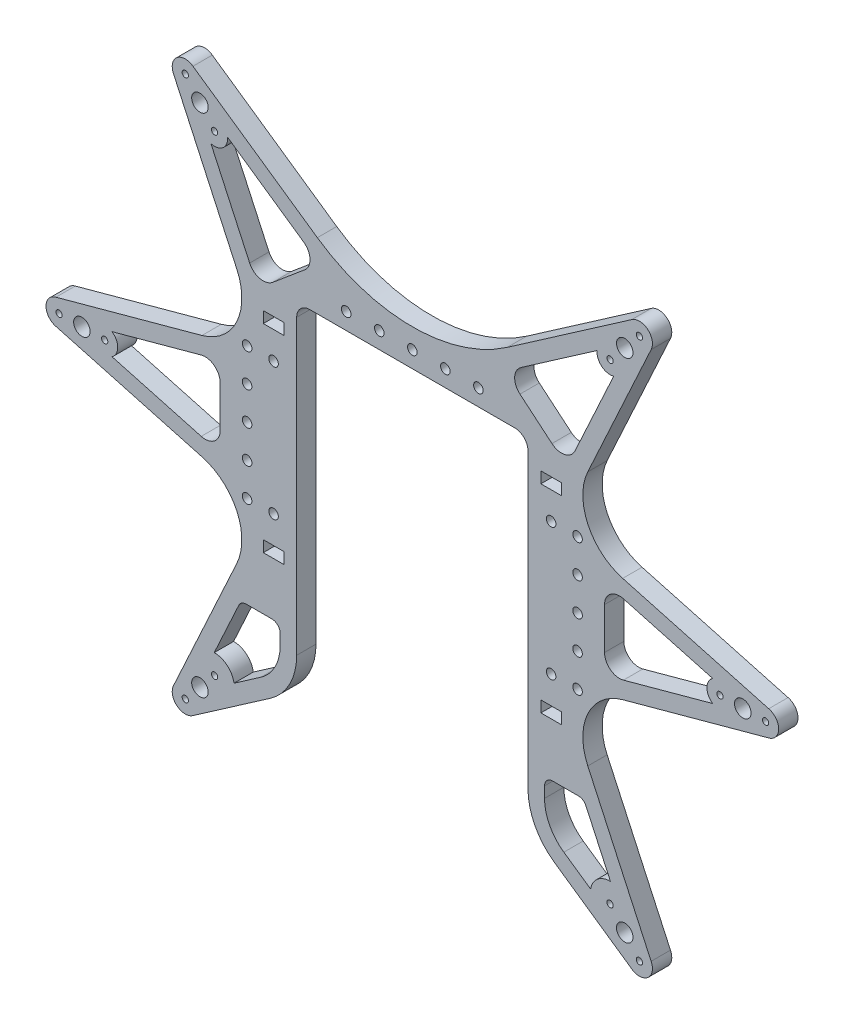
SolidWorks part; units mm, degrees
material "Acrylic (Medium-high impact)"
ref_plane "Front Plane" through (0, 0, 0) normal (0, 0, 1) x (1, 0, 0)
ref_plane "Top Plane" through (0, 0, 0) normal (0, 1, 0) x (1, 0, 0)
ref_plane "Right Plane" through (0, 0, 0) normal (1, 0, 0) x (0, 0, -1)
sketch "Sketch1" plane through (0, 0, 0) normal (0, 0, 1) x (1, 0, 0)
  line L0 (587.1768, 489.0962) -> (587.1768, 412.0041) construction
  line L1 (549.3782, 453.8298) -> (576.3894, 461.205)
  line L2 (601.3767, 418.8158) -> (595.1767, 422.2158) construction
  line L3 (590.0159, 402.7396) -> (597.7767, 402.7396)
  line L4 (600.2767, 396.9582) -> (600.2767, 400.2396)
  line L5 (601.3767, 422.2158) -> (595.1767, 418.8158) construction
  line L6 (532.4267, 446.7161) -> (532.4267, 450.5502) construction
  line L7 (576.6167, 434.6502) -> (532.4267, 446.7161)
  line L8 (635.7171, 455.9841) -> (-31503.6634, 38758.2062) construction
  line L9 (532.4267, 450.5502) -> (532.4267, 454.3842) construction
  line L10 (601.3767, 422.2158) -> (601.3767, 418.8158)
  line L11 (601.3767, 422.2158) -> (595.1767, 422.2158)
  line L12 (595.1767, 422.2158) -> (595.1767, 418.8158)
  line L13 (549.3782, 447.2706) -> (576.3894, 439.8953)
  line L14 (575.9979, 527.1546) -> (571.5627, 532.4403) construction
  line L15 (575.9979, 527.1546) -> (580.4331, 521.8689) construction
  line L16 (601.3767, 418.8158) -> (595.1767, 418.8158)
  line L17 (576.6167, 466.4501) -> (576.6167, 434.6502) construction
  line L18 (694.2433, 380.1612) -> (686.125, 385.7883)
  line L19 (570.952, 533.1681) -> (573.8891, 535.6326) construction
  line L20 (-358.0106, 400.5502) -> (49641.9894, 400.5502) construction
  line L21 (540.2767, 450.5502) -> (547.1767, 450.5502) construction
  line L22 (-351.1587, 450.5502) -> (49648.8413, 450.5502) construction
  line L23 (680.2767, 396.9582) -> (680.2767, 400.2396)
  line L24 (582.1207, 456.8289) -> (582.1207, 444.2715)
  line L25 (685.3767, 482.2502) -> (679.1767, 478.8502) construction
  line L26 (587.1768, 489.0962) -> (568.0149, 530.7036)
  line L27 (690.5374, 402.7396) -> (682.7767, 402.7396)
  line L28 (700.2251, 385.1805) -> (692.8082, 401.2854)
  line L29 (685.3767, 478.8502) -> (679.1767, 482.2502) construction
  line L30 (611.5369, 509.5368) -> (573.8891, 535.6326)
  line L31 (568.0149, 530.7036) -> (570.952, 533.1681) construction
  line L32 (610.8062, 450.5502) -> (605.2767, 450.5502) construction
  line L33 (605.2767, 489.5502) -> (675.2767, 489.5502)
  line L34 (663.4579, 478.1765) -> (-31475.9226, -37824.0456) construction
  line L35 (540.2767, 450.5502) -> (533.3767, 450.5502) construction
  line L36 (576.6167, 466.4501) -> (532.4267, 454.3842)
  line L37 (575.9979, 373.9457) -> (571.5627, 368.66) construction
  line L38 (683.2767, 381.679) -> (706.6642, 365.4678)
  line L39 (709.6013, 367.9323) -> (712.5384, 370.3968) construction
  line L40 (580.3282, 385.1805) -> (587.7451, 401.2854)
  line L41 (640.2767, 450.5502) -> (675.2767, 450.5502) construction
  line L42 (706.6642, 365.4678) -> (709.6013, 367.9323) construction
  line L43 (704.5554, 373.9457) -> (700.1202, 379.2314) construction
  line L44 (704.5554, 373.9457) -> (708.9906, 368.66) construction
  line L45 (740.2767, 450.5502) -> (747.1767, 450.5502) construction
  line L46 (586.31, 380.1612) -> (594.4283, 385.7883)
  line L47 (669.7471, 450.5502) -> (675.2767, 450.5502) construction
  line L48 (575.9979, 373.9457) -> (580.4331, 379.2314) construction
  line L49 (587.1768, 412.0041) -> (568.0149, 370.3968)
  line L50 (712.5384, 530.7036) -> (709.6013, 533.1681) construction
  line L51 (740.2767, 450.5502) -> (733.3767, 450.5502) construction
  line L52 (573.8891, 365.4678) -> (570.952, 367.9323) construction
  line L53 (570.952, 367.9323) -> (568.0149, 370.3968) construction
  line L54 (709.6013, 533.1681) -> (706.6642, 535.6326) construction
  line L55 (597.2767, 381.679) -> (573.8891, 365.4678)
  line L56 (703.9366, 466.4501) -> (703.9366, 434.6502) construction
  line L58 (704.5554, 527.1546) -> (700.1202, 521.8689) construction
  line L59 (704.5554, 527.1546) -> (708.9906, 532.4403) construction
  line L60 (748.1267, 450.5502) -> (748.1267, 454.3842) construction
  line L61 (748.1267, 446.7161) -> (748.1267, 450.5502) construction
  line L62 (1630.6528, 450.5502) -> (-48369.3472, 450.5502) construction
  line L63 (691.7267, 450.5502) -> (588.8267, 450.5502) construction
  line L64 (679.1767, 422.2158) -> (685.3767, 418.8158) construction
  line L67 (693.3765, 489.0962) -> (693.3765, 412.0041) construction
  line L68 (-358.708, 500.5502) -> (49641.292, 500.5502) construction
  line L69 (579.336, 518.0744) -> (591.0486, 492.6418)
  line L70 (679.1767, 418.8158) -> (685.3767, 422.2158) construction
  line L71 (685.3767, 478.8502) -> (685.3767, 482.2502)
  line L72 (605.2767, 489.5502) -> (605.2767, 396.9582)
  line L73 (584.3606, 522.2905) -> (607.3728, 506.3395)
  line L74 (607.7017, 499.196) -> (598.0264, 491.0775)
  line L75 (685.3767, 478.8502) -> (679.1767, 478.8502)
  line L76 (679.1767, 478.8502) -> (679.1767, 482.2502)
  line L77 (672.8516, 499.196) -> (682.5269, 491.0775)
  line L78 (696.1927, 522.2905) -> (673.1805, 506.3395)
  line L79 (675.2767, 489.5502) -> (675.2767, 396.9582)
  line L81 (701.2173, 518.0744) -> (689.5047, 492.6418)
  line L83 (693.3765, 412.0041) -> (712.5384, 370.3968)
  line L87 (703.9366, 466.4501) -> (748.1267, 454.3842)
  line L88 (669.0164, 509.5368) -> (706.6642, 535.6326)
  line L89 (693.3765, 489.0962) -> (712.5384, 530.7036)
  line L90 (698.4326, 456.8289) -> (698.4326, 444.2715)
  line L91 (685.3767, 482.2502) -> (679.1767, 482.2502)
  line L92 (731.1751, 447.2706) -> (704.1639, 439.8953)
  line L93 (679.1767, 418.8158) -> (685.3767, 418.8158)
  line L94 (685.3767, 422.2158) -> (685.3767, 418.8158)
  line L95 (679.1767, 422.2158) -> (685.3767, 422.2158)
  line L96 (703.9366, 434.6502) -> (748.1267, 446.7161)
  line L97 (731.1751, 453.8298) -> (704.1639, 461.205)
  line L98 (679.1767, 422.2158) -> (679.1767, 418.8158)
  line L100 (590.2767, 450.5502) -> (590.2767, 460.5502) construction
  line L102 (640.2767, 494.5502) -> (630.2767, 494.5502) construction
  line L104 (568.9811, 521.2669) -> (581.557, 531.8192) construction
  line L111 (640.2767, -500.116) -> (640.2767, 49499.884) construction
  line L157 (595.1767, 482.2502) -> (601.3767, 482.2502)
  line L158 (601.3767, 478.8502) -> (601.3767, 482.2502)
  line L159 (595.1767, 478.8502) -> (601.3767, 482.2502) construction
  line L162 (595.1767, 482.2502) -> (601.3767, 478.8502) construction
  line L163 (595.1767, 478.8502) -> (601.3767, 478.8502)
  line L164 (595.1767, 478.8502) -> (595.1767, 482.2502)
  circle A0 centre (533.3767, 450.5502) radius 0.95
  arc A1 (582.1207, 444.2715) -> (576.3894, 439.8953) centre (577.5843, 444.2715) cw
  circle A2 centre (575.9979, 527.1546) radius 2.5
  circle A3 centre (547.1767, 450.5502) radius 0.95
  arc A4 (549.3782, 447.2706) -> (549.3782, 453.8298) centre (547.1767, 450.5502) ccw
  circle A5 centre (540.2767, 450.5502) radius 2.5
  arc A6 (532.4267, 446.7161) -> (532.4267, 454.3842) centre (533.3767, 450.5502) cw
  circle A7 centre (590.2767, 460.5502) radius 1.45
  circle A8 centre (571.5627, 532.4403) radius 0.95
  circle A9 centre (580.4331, 521.8689) radius 0.95
  arc A10 (579.336, 518.0744) -> (584.3606, 522.2905) centre (580.4331, 521.8689) ccw
  arc A11 (582.1207, 456.8289) -> (576.3894, 461.205) centre (577.5843, 456.8289) ccw
  arc A12 (600.2767, 400.2396) -> (597.7767, 402.7396) centre (597.7767, 400.2396) ccw
  circle A13 centre (682.2767, 470.5502) radius 1.45
  arc A14 (586.31, 380.1612) -> (580.3282, 385.1805) centre (580.4331, 379.2314) ccw
  arc A15 (568.0149, 530.7036) -> (573.8891, 535.6326) centre (571.5627, 532.4403) cw
  arc A16 (605.2767, 396.9582) -> (597.2767, 381.679) centre (586.6858, 396.9582) cw
  arc A17 (600.2767, 396.9582) -> (594.4283, 385.7883) centre (586.6858, 396.9582) cw
  arc A18 (587.7451, 401.2854) -> (590.0159, 402.7396) centre (590.0159, 400.2396) cw
  arc A19 (675.2767, 396.9582) -> (683.2767, 381.679) centre (693.8675, 396.9582) ccw
  circle A20 centre (630.2767, 494.5502) radius 1.45
  circle A21 centre (620.2767, 494.5502) radius 1.45
  arc A22 (680.2767, 396.9582) -> (686.125, 385.7883) centre (693.8675, 396.9582) ccw
  arc A23 (680.2767, 400.2396) -> (682.7767, 402.7396) centre (682.7767, 400.2396) cw
  arc A24 (692.8082, 401.2854) -> (690.5374, 402.7396) centre (690.5374, 400.2396) ccw
  arc A25 (694.2433, 380.1612) -> (700.2251, 385.1805) centre (700.1202, 379.2314) cw
  circle A27 centre (580.4331, 379.2314) radius 0.95
  circle A28 centre (575.9979, 373.9457) radius 2.5
  circle A29 centre (571.5627, 368.66) radius 0.95
  arc A30 (573.8891, 365.4678) -> (568.0149, 370.3968) centre (571.5627, 368.66) cw
  arc A31 (611.5369, 509.5368) -> (669.0164, 509.5368) centre (640.2767, 550.9991) ccw
  arc A35 (576.6167, 434.6502) -> (587.1768, 412.0041) centre (572.3036, 418.8538) cw
  arc A36 (598.0264, 491.0775) -> (591.0486, 492.6418) centre (595.1348, 494.5236) cw
  arc A37 (607.7017, 499.196) -> (607.3728, 506.3395) centre (604.8101, 502.6422) ccw
  arc A38 (576.6167, 466.4501) -> (587.1768, 489.0962) centre (572.3036, 482.2466) ccw
  circle A40 centre (590.2767, 430.5502) radius 1.45
  circle A42 centre (590.2767, 440.5502) radius 1.45
  arc A44 (703.9366, 466.4501) -> (693.3765, 489.0962) centre (708.2497, 482.2466) cw
  arc A45 (672.8516, 499.196) -> (673.1805, 506.3395) centre (675.7432, 502.6422) cw
  arc A46 (682.5269, 491.0775) -> (689.5047, 492.6418) centre (685.4185, 494.5236) ccw
  arc A47 (703.9366, 434.6502) -> (693.3765, 412.0041) centre (708.2497, 418.8538) ccw
  circle A49 centre (590.2767, 470.5502) radius 1.45
  circle A50 centre (682.2767, 430.5502) radius 1.45
  arc A51 (706.6642, 365.4678) -> (712.5384, 370.3968) centre (708.9906, 368.66) ccw
  circle A52 centre (708.9906, 368.66) radius 0.95
  circle A53 centre (704.5554, 373.9457) radius 2.5
  circle A54 centre (700.1202, 379.2314) radius 0.95
  circle A58 centre (660.2767, 494.5502) radius 1.45
  circle A59 centre (650.2767, 494.5502) radius 1.45
  arc A63 (712.5384, 530.7036) -> (706.6642, 535.6326) centre (708.9906, 532.4403) ccw
  arc A66 (698.4326, 456.8289) -> (704.1639, 461.205) centre (702.969, 456.8289) cw
  arc A67 (701.2173, 518.0744) -> (696.1927, 522.2905) centre (700.1202, 521.8689) cw
  circle A68 centre (700.1202, 521.8689) radius 0.95
  circle A69 centre (708.9906, 532.4403) radius 0.95
  circle A70 centre (690.2767, 450.5502) radius 1.45
  arc A71 (748.1267, 446.7161) -> (748.1267, 454.3842) centre (747.1767, 450.5502) ccw
  circle A72 centre (740.2767, 450.5502) radius 2.5
  arc A74 (731.1751, 447.2706) -> (731.1751, 453.8298) centre (733.3767, 450.5502) cw
  circle A75 centre (733.3767, 450.5502) radius 0.95
  circle A76 centre (704.5554, 527.1546) radius 2.5
  arc A77 (698.4326, 444.2715) -> (704.1639, 439.8953) centre (702.969, 444.2715) ccw
  circle A78 centre (747.1767, 450.5502) radius 0.95
  circle A81 centre (690.2767, 470.5502) radius 1.45
  circle A82 centre (640.2767, 494.5502) radius 1.45
  circle A83 centre (690.2767, 440.5502) radius 1.45
  circle A84 centre (690.2767, 430.5502) radius 1.45
  circle A86 centre (690.2767, 460.5502) radius 1.45
  circle A89 centre (590.2767, 450.5502) radius 1.45
  circle A92 centre (598.2767, 430.5502) radius 1.45
  circle A129 centre (598.2767, 470.5502) radius 1.45
  circle A130 centre (590.2767, 480.5502) radius 1.45 [skipped]
  point P0 (640.2767, 500.5502)
  point P1 (640.2767, 400.5502)
  point P23 (599.5444, 402.0074)
  point P25 (598.2767, 420.5158)
  point P46 (582.1207, 450.5502)
  point P48 (584.2577, 383.7894)
  point P54 (602.8641, 495.1368)
  point P55 (582.9721, 518.843)
  point P64 (582.1207, 450.5502)
  point P104 (640.2767, 489.5502)
  point P124 (602.8641, 495.1368)
  point P157 (696.2956, 383.7894)
  point P229 (677.6892, 495.1368)
  point P231 (698.4326, 450.5502)
  point P238 (640.2767, 489.5502)
  point P242 (569.0236, 535.4662)
  point P307 (640.2767, 500.5502)
  point P366 (598.2767, 480.5502)
  dimension "D6" = 1.9
  dimension "D9" = 42
  dimension "D7" = 2.9
  dimension "D11" = 5
  dimension "D12" = 13.8
  dimension "D5" = 50
  dimension "D14" = 20
  dimension "D15" = 50
  dimension "D16" = 4
  dimension "D17" = 3
  dimension "D18" = 5
  dimension "D19" = 75
  dimension "D20" = 2.9
  dimension "D13" = 70
  dimension "D27" = 28
  dimension "D8" = 1.9
  dimension "D36" = 3
  dimension "D37" = 3
  dimension "D29" = 1.9
  dimension "D47" = 5
  dimension "D28" = 3
  dimension "D25" = 3
  dimension "D38" = 3
  dimension "D39" = 5
  dimension "D26" = 2.5
  dimension "D52" = 5
  dimension "D50" = 5
  dimension "D51" = 39
  dimension "D10" = 10
  dimension "D21" = 44
  dimension "D22" = 13.8
  dimension "D23" = 8
  dimension "D24" = 5
  dimension "D30" = 13.8
  dimension "D31" = 75
  dimension "D32" = 100
  dimension "D33" = 50
  dimension "D34" = 6.2
  dimension "D35" = 100
  dimension "D40" = 100
  dimension "D41" = 5
  dimension "D42" = 5
  dimension "D43" = 100
  dimension "D44" = 3.4
  dimension "D53" = 10
  dimension "D56" = 10
  dimension "D59" = 5
  dimension "D61" = 28
extrude "Boss-Extrude1" add sketch "Sketch1" along normal blind 5.85
fillet "Fillet1" radius 4 2 edges at (675.2767, 489.5502, 2.925) (605.2767, 489.5502, 2.925)
